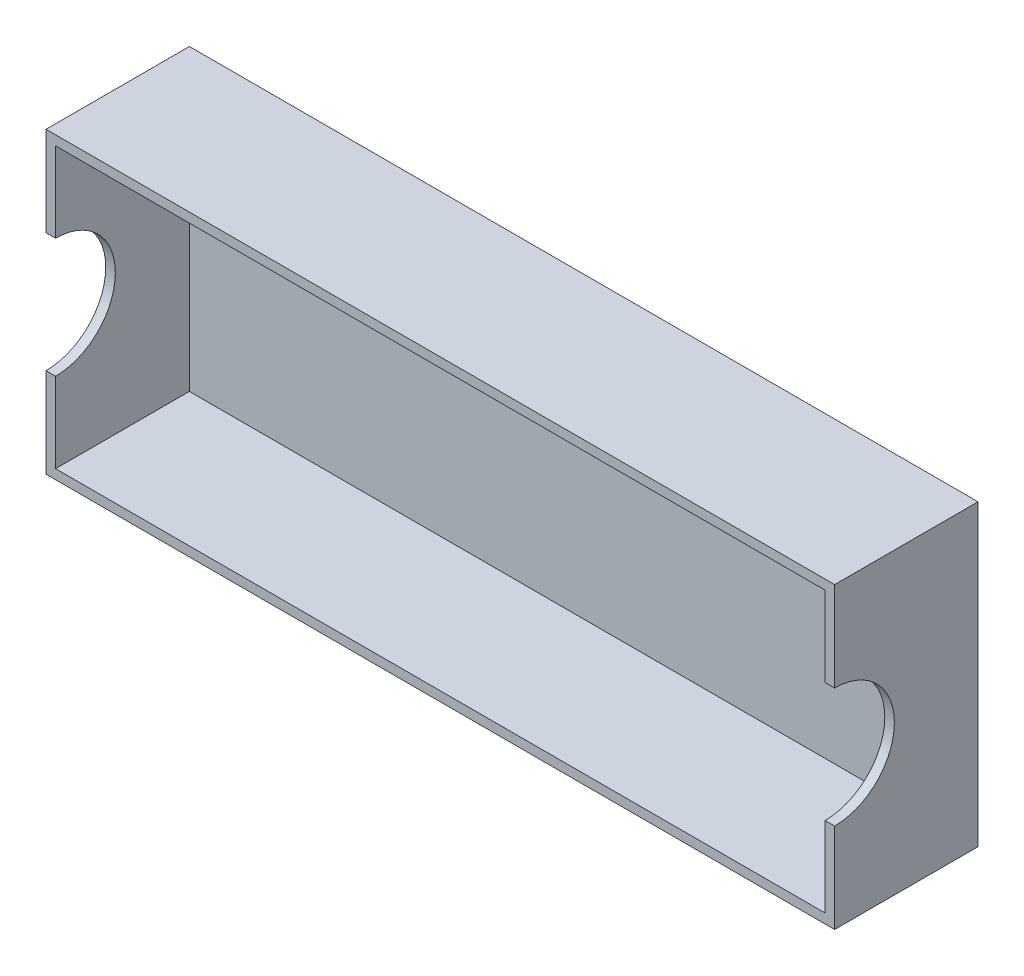
SolidWorks part; units mm, degrees
ref_plane "Front Plane" through (0, 0, 0) normal (0, 0, 1) x (1, 0, 0)
ref_plane "Top Plane" through (0, 0, 0) normal (0, 1, 0) x (1, 0, 0)
ref_plane "Right Plane" through (0, 0, 0) normal (1, 0, 0) x (0, 0, -1)
sketch "Sketch2" plane through (0, 0, 0) normal (0, 0, 1) x (1, 0, 0)
  line L1 (-33, 12.5) -> (33, 12.5)
  line L2 (-33, 12.5) -> (-33, -12.5)
  line L3 (-33, -12.5) -> (33, -12.5)
  line L4 (33, 12.5) -> (33, -12.5)
  line L5 (-33, 12.5) -> (33, -12.5) construction
  line L6 (-33, -12.5) -> (33, 12.5) construction
  point P0 (0, 0)
  dimension "D1" = 25
  dimension "D2" = 66
extrude "Boss-Extrude1" add sketch "Sketch2" along normal blind 12
sketch "Sketch3" plane through (0, 0, 12) normal (0, 0, 1) x (1, 0, 0)
  line L0 (33, 12.5) -> (-33, 12.5) construction
  line L1 (-32.2, 11.7) -> (32.2, 11.7)
  line L2 (-32.2, 11.7) -> (-32.2, -11.7)
  line L3 (-32.2, -11.7) -> (32.2, -11.7)
  line L4 (32.2, 11.7) -> (32.2, -11.7)
  line L5 (-32.2, 11.7) -> (32.2, -11.7) construction
  line L6 (-32.2, -11.7) -> (32.2, 11.7) construction
  line L7 (33, -12.5) -> (33, 12.5) construction
  point P0 (0, 0)
  dimension "D1" = 0.8
  dimension "D2" = 0.8
extrude "Cut-Extrude1" cut sketch "Sketch3" against normal blind 11.2
sketch "Sketch5" plane through (33, 0, 0) normal (1, 0, 0) x (0, 0, -1)
  line L0 (-12, -12.5) -> (-12, 12.5) construction
  circle A0 centre (-12, 0) radius 5
  dimension "D1" = 10
extrude "Cut-Extrude2" cut sketch "Sketch5" against normal through all
